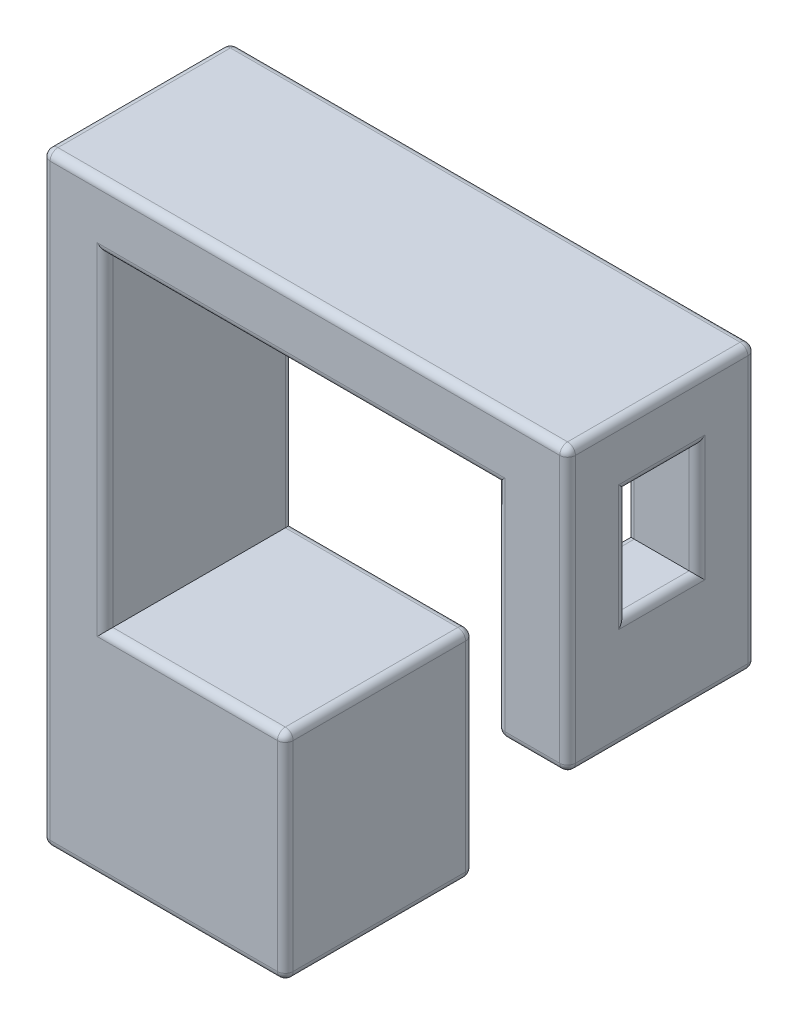
SolidWorks part; units mm, degrees
ref_plane "Front Plane" through (0, 0, 0) normal (0, 0, 1) x (1, 0, 0)
ref_plane "Top Plane" through (0, 0, 0) normal (0, 1, 0) x (1, 0, 0)
ref_plane "Right Plane" through (0, 0, 0) normal (1, 0, 0) x (0, 0, -1)
sketch "Sketch1" plane through (0, 0, 0) normal (0, 0, 1) x (1, 0, 0)
  line L0 (0, 0) -> (-23, 0)
  line L4 (-23, 27.5) -> (0, 27.5)
  line L5 (0, 27.5) -> (0, 0)
  line L7 (-23, 69) -> (27, 69)
  line L8 (27, 69) -> (27, 41)
  line L9 (27, 41) -> (36, 41)
  line L10 (36, 41) -> (36, 77)
  line L11 (36, 77) -> (-23.4049, 77)
  line L12 (-23, 0) -> (-31, 0)
  line L13 (-31, 0) -> (-31, 77)
  line L14 (-31, 77) -> (-23.4049, 77)
  line L15 (-23, 69) -> (-23, 27.5)
  dimension "D1" = 23
  dimension "D2" = 27.5
  dimension "D3" = 8
  dimension "D4" = 41.5
  dimension "D7" = 50
  dimension "D8" = 28
  dimension "D9" = 8
  dimension "D10" = 9
extrude "Boss-Extrude1" add sketch "Sketch1" along normal mid plane 24
hole_wizard "Ø2.7 (2.7) Diameter Hole1" positions "Sketch2" profile "Sketch3" hole size "Ø2.7" standard "ANSI Metric"
sketch "Sketch2" plane through (0, 39.5, 0) normal (0, 1, 0) x (1, 0, 0)
  line L0 (-16, -12) -> (-16, 12) construction
  line L1 (32.5, -12) -> (-31, -12) construction
  point P0 (-20, 4.75)
  point P2 (-20, -4.75)
  dimension "D1" = 9.5
  dimension "D2" = 4
  dimension "D3" = 7.25
sketch "Sketch3" plane through (-20, 39.5, -4.75) normal (1, 0, 0) x (0, 0, 1)
  line L0 (0, 0) -> (0, 8.8112)
  line L1 (0, 8.8112) -> (1.35, 8)
  line L2 (1.35, 8) -> (1.35, 0.025)
  line L3 (1.35, 0.025) -> (1.375, 0)
  line L5 (1.375, 0) -> (0, 0)
  line L6 (-1.35, 0.025) -> (-1.375, 0) construction
  line L10 (0, 8.8112) -> (-1.35, 8) construction
  line L11 (0, -6.35) -> (0, 107.95) construction
  dimension "Hole Dia." = 2.7
  dimension "Hole Depth" = 8
  dimension "Near C'Sink Dia." = 2.75
  dimension "Near C'Sink Angle" = 90
  dimension "Drill Angle" = 118
hole_wizard "Ø4.8 (4.8) Diameter Hole1" positions "Sketch4" profile "Sketch5" hole size "Ø4.8" standard "ANSI Metric"
sketch "Sketch4" plane through (0, 41, 0) normal (0, -1, 0) x (-1, 0, 0)
  line L1 (-27, 12) -> (-36, 12) construction
  line L2 (-27, -12) -> (-27, 12) construction
  point P0 (-31.3, 4.875)
  point P2 (-31.3, -4.875)
  dimension "D1" = 9.75
  dimension "D2" = 4.3
  dimension "D3" = 7.125
sketch "Sketch5" plane through (31.3, 41, -4.875) normal (1, 0, 0) x (0, 0, -1)
  line L0 (0, 0) -> (0, 9.4421)
  line L1 (0, 9.4421) -> (2.4, 8)
  line L2 (2.4, 8) -> (2.4, 0)
  line L5 (2.4, 0) -> (0, 0)
  line L10 (0, 9.4421) -> (-2.4, 8) construction
  line L11 (0, -6.35) -> (0, 107.95) construction
  dimension "Hole Dia." = 4.8
  dimension "Hole Depth" = 8
  dimension "Drill Angle" = 118
sketch "Sketch10" plane through (0, 0, 0) normal (0, -1, 0) x (-1, 0, 0)
  line L0 (31, -12) -> (31, 12) construction
  line L1 (31, 12) -> (0, 12) construction
  point P0 (5.95, 0)
  point P2 (21.95, 0)
  dimension "D1" = 16
  dimension "D2" = 9.05
  dimension "D3" = 12
hole_wizard "Ø4.8 (4.8) Diameter Hole2" positions "Sketch10" profile "Sketch9" hole size "Ø4.8" standard "ANSI Metric"
sketch "Sketch9" plane through (-5.95, 0, 0) normal (1, 0, 0) x (0, 0, -1)
  line L0 (0, 0) -> (0, 9.4421)
  line L1 (0, 9.4421) -> (2.4, 8)
  line L2 (2.4, 8) -> (2.4, 0)
  line L5 (2.4, 0) -> (0, 0)
  line L10 (0, 9.4421) -> (-2.4, 8) construction
  line L11 (0, -6.35) -> (0, 107.95) construction
  dimension "Hole Dia." = 4.8
  dimension "Hole Depth" = 8
  dimension "Drill Angle" = 118
sketch "Sketch11" plane through (36, 0, 0) normal (1, 0, 0) x (0, 0, -1)
  line L0 (-12, 77) -> (12, 77) construction
  line L1 (-4.5, 69) -> (4.5, 69)
  line L2 (-4.5, 69) -> (-4.5, 55)
  line L3 (-4.5, 55) -> (4.5, 55)
  line L4 (4.5, 69) -> (4.5, 55)
  line L5 (-12, 41) -> (-12, 77) construction
  dimension "D1" = 8
  dimension "D2" = 14
  dimension "D3" = 9
  dimension "D4" = 7.5
extrude "Cut-Extrude1" cut sketch "Sketch11" against normal up to next
fillet "Fillet1" radius 1 34 edges at (0, 0, 0) (0, 27.5, 0) (-11.5, 27.5, -12) (2, 69, -12) (27, 55, -12) (31.5, 41, -12) (36, 59, -12) (2.5, 77, -12) (-15.5, 0, -12) (0, 13.75, -12) (-31, 77, 0) (-31, 0, 0) (-31, 38.5, -12) (-15.5, 0, 12) (-31, 38.5, 12) (2.5, 77, 12) (36, 59, 12) (31.5, 41, 12) (27, 55, 12) (2, 69, 12) (-11.5, 27.5, 12) (0, 13.75, 12) (36, 77, 0) (36, 41, 0) (36, 62, -4.5) (36, 69, 0) (36, 62, 4.5) (36, 55, 0) (-23, 48.25, -12) (-23, 48.25, 12) (27, 62, -4.5) (27, 55, 0) (27, 62, 4.5) (27, 41, 0)
